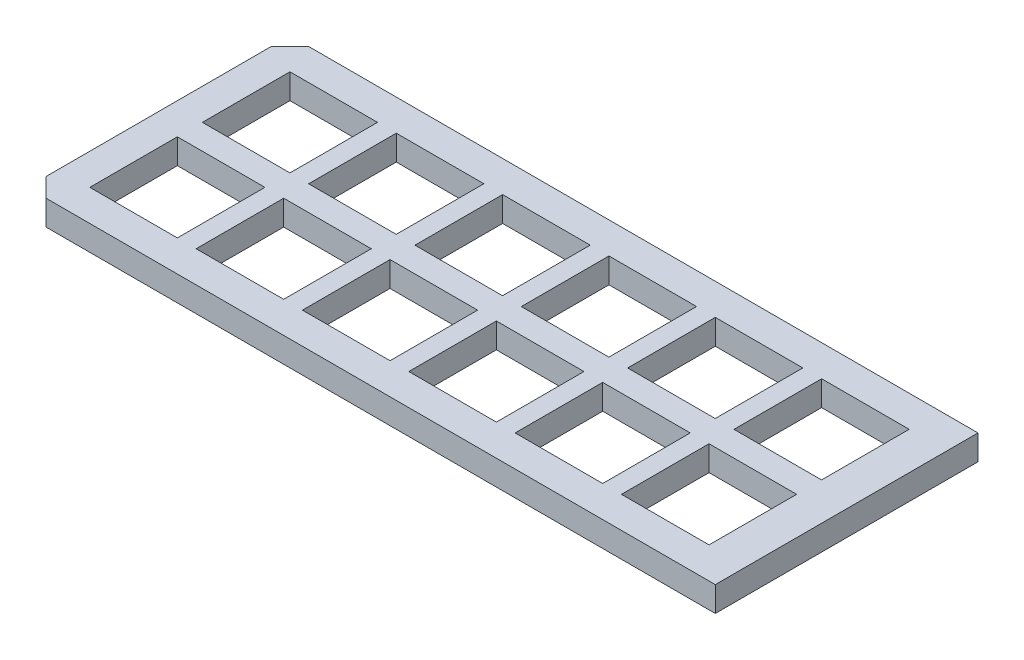
SolidWorks part; units mm, degrees
material "Сосна"
ref_plane "Спереди" through (0, 0, 0) normal (0, 0, 1) x (1, 0, 0)
ref_plane "Сверху" through (0, 0, 0) normal (0, 1, 0) x (1, 0, 0)
ref_plane "Справа" through (0, 0, 0) normal (1, 0, 0) x (0, 0, -1)
sketch3d "Трехмерный эскиз1"
  line L10 (-80.8457, 0, 24.8217) -> (26.1543, 0, 24.8217)
  line L11 (-83.8457, 0, 21.8217) -> (-80.8457, 0, 24.8217)
  line L16 (-83.8457, 0, 21.8217) -> (-83.8457, 0, -14.1783)
  line L17 (-83.8457, 0, -14.1783) -> (-80.8457, 0, -17.1783)
  line L22 (-80.8457, 0, -17.1783) -> (26.1543, 0, -17.1783)
  line L23 (-78.8457, 0, -12.1783) -> (-64.8457, 0, -12.1783)
  line L28 (-78.8457, 0, 1.8217) -> (-78.8457, 0, -12.1783)
  line L29 (-78.8457, 0, 1.8217) -> (-64.8457, 0, 1.8217)
  line L34 (-64.8457, 0, 1.8217) -> (-64.8457, 0, -12.1783)
  line L35 (-78.8457, 0, 5.8217) -> (-64.8457, 0, 5.8217)
  line L41 (-64.8457, 0, 19.8217) -> (-64.8457, 0, 5.8217)
  line L42 (-78.8457, 0, 19.8217) -> (-78.8457, 0, 5.8217)
  line L46 (-78.8457, 0, 19.8217) -> (-64.8457, 0, 19.8217)
  line L47 (-61.8457, 0, 19.8217) -> (-61.8457, 0, 5.8217)
  line L52 (-61.8457, 0, 19.8217) -> (-47.8457, 0, 19.8217)
  line L53 (-47.8457, 0, 19.8217) -> (-47.8457, 0, 5.8217)
  line L58 (-61.8457, 0, 5.8217) -> (-47.8457, 0, 5.8217)
  line L59 (-44.8457, 0, 19.8217) -> (-44.8457, 0, 5.8217)
  line L64 (-44.8457, 0, 5.8217) -> (-30.8457, 0, 5.8217)
  line L65 (-30.8457, 0, 19.8217) -> (-30.8457, 0, 5.8217)
  line L70 (-44.8457, 0, 19.8217) -> (-30.8457, 0, 19.8217)
  line L71 (-27.8457, 0, 19.8217) -> (-13.8457, 0, 19.8217)
  line L93 (-27.8457, 0, 19.8217) -> (-27.8457, 0, 5.8217)
  line L94 (-27.8457, 0, 5.8217) -> (-13.8457, 0, 5.8217)
  line L167 (-13.8457, 0, 19.8217) -> (-13.8457, 0, 5.8217)
  line L168 (26.1543, 0, 24.8217) -> (26.1543, 0, -17.1783)
  line L169 (20.1543, 0, 19.8217) -> (20.1543, 0, 5.8217)
  line L170 (6.1543, 0, 5.8217) -> (20.1543, 0, 5.8217)
  line L171 (6.1543, 0, 19.8217) -> (6.1543, 0, 5.8217)
  line L172 (6.1543, 0, 19.8217) -> (20.1543, 0, 19.8217)
  line L173 (-10.8457, 0, 19.8217) -> (3.1543, 0, 19.8217)
  line L174 (3.1543, 0, 19.8217) -> (3.1543, 0, 5.8217)
  line L175 (-10.8457, 0, 19.8217) -> (-10.8457, 0, 5.8217)
  line L176 (-10.8457, 0, 5.8217) -> (3.1543, 0, 5.8217)
  line L177 (-10.8457, 0, 1.8338) -> (3.1543, 0, 1.8338)
  line L178 (3.1543, 0, 1.8338) -> (3.1543, 0, -12.1783)
  line L179 (-10.8457, 0, -12.1783) -> (3.1543, 0, -12.1783)
  line L180 (6.1543, 0, 1.8338) -> (6.1543, 0, -12.1783)
  line L181 (6.1543, 0, 1.8338) -> (20.1543, 0, 1.8338)
  line L182 (20.1543, 0, 1.8338) -> (20.1543, 0, -12.1783)
  line L183 (6.1543, 0, -12.1783) -> (20.1543, 0, -12.1783)
  line L184 (-13.8457, 0, 1.8338) -> (-13.8457, 0, -12.1783)
  line L185 (-27.8457, 0, 1.8338) -> (-13.8457, 0, 1.8338)
  line L186 (-10.8457, 0, 1.8338) -> (-10.8457, 0, -12.1783)
  line L187 (-27.8457, 0, -12.1783) -> (-13.8457, 0, -12.1783)
  line L188 (-27.8457, 0, 1.8338) -> (-27.8457, 0, -12.1783)
  line L189 (-30.8457, 0, 1.8338) -> (-30.8457, 0, -12.1783)
  line L190 (-44.8457, 0, 1.8338) -> (-30.8457, 0, 1.8338)
  line L191 (-44.8457, 0, 1.8338) -> (-44.8457, 0, -12.1783)
  line L192 (-44.8457, 0, -12.1783) -> (-30.8457, 0, -12.1783)
  line L193 (-47.8457, 0, 1.8338) -> (-47.8457, 0, -12.1783)
  line L194 (-61.8457, 0, -12.1783) -> (-47.8457, 0, -12.1783)
  line L195 (-61.8457, 0, 1.8338) -> (-61.8457, 0, -12.1783)
  line L196 (-61.8457, 0, 1.8338) -> (-47.8457, 0, 1.8338)
  point P114 (-83.3137, -1.0149, -16.6463)
  point P263 (-83.8457, 0, -14.1783)
  point P264 (-83.8457, 0, -14.1783)
  point P265 (-83.8457, 0, -14.1783)
  point P267 (-80.8457, 0, 24.8217)
  dimension "D1" = 107
  dimension "D7" = 14
  dimension "D2" = 4.2426
  dimension "D3" = 4.2426
  dimension "D4" = 36
  dimension "D5" = 42
  dimension "D6" = 14
  dimension "D11" = 3
  dimension "D8" = 3.9879
  dimension "D9" = 5
  dimension "D10" = 5
  dimension "D12" = 5
extrude "Бобышка-Вытянуть1" add sketch "Трехмерный эскиз1" along direction (0, 1, 0) on the side against the normal blind 4
